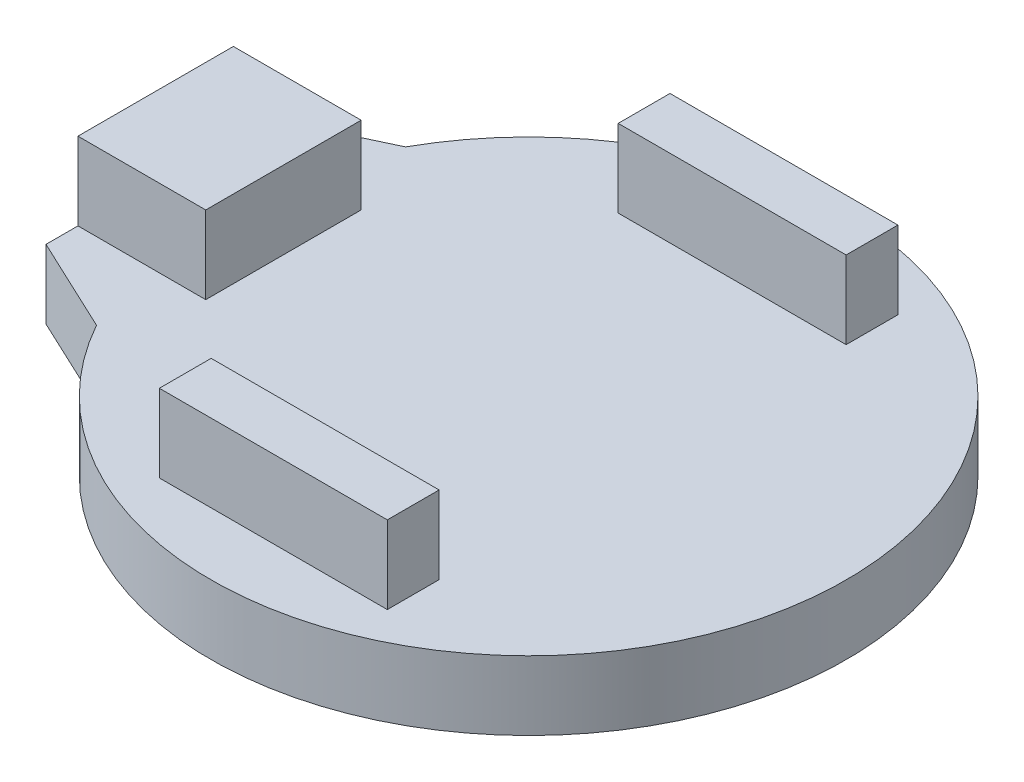
SolidWorks part; units mm, degrees
ref_plane "Front Plane" through (0, 0, 0) normal (0, 0, 1) x (1, 0, 0)
ref_plane "Top Plane" through (0, 0, 0) normal (0, 1, 0) x (1, 0, 0)
ref_plane "Right Plane" through (0, 0, 0) normal (1, 0, 0) x (0, 0, -1)
sketch "Sketch1" plane through (0, 0, 0) normal (0, 1, 0) x (1, 0, 0)
  line L0 (18.4, 0) -> (18.4, 26.4174) construction
  line L1 (-15.2, -6.35) -> (-17.2696, -6.35) construction
  line L2 (-15.2, -6.35) -> (-15.2, 6.35) construction
  line L3 (-17.2696, 6.35) -> (-21.6, 6.35) construction
  line L4 (-21.6, -6.35) -> (-21.6, 6.35)
  line L5 (-18.4, 0) -> (-21.6, 6.35) construction
  line L6 (-18.4, 0) -> (-21.6, -6.35) construction
  line L7 (-21.6, 6.35) -> (-16.0794, 8.9449)
  line L8 (-21.6, -6.35) -> (-16.0794, -8.9449)
  line L9 (-15.2, 6.35) -> (-17.2696, 6.35) construction
  line L10 (-15.2, 6.35) -> (-18.4, 0) construction
  line L11 (-15.2, -6.35) -> (-18.4, 0) construction
  line L12 (-17.2696, -6.35) -> (-21.6, -6.35) construction
  arc A0 (-16.0794, -8.9449) -> (-16.0794, 8.9449) centre (0, 0) ccw
  arc A1 (-16.0794, 8.9449) -> (-17.2696, 6.35) centre (0, 0) ccw construction
  arc A2 (-17.2696, 6.35) -> (-18.4, 0) centre (0, 0) ccw construction
  arc A3 (-18.4, 0) -> (-17.2696, -6.35) centre (0, 0) ccw construction
  arc A4 (-17.2696, -6.35) -> (-16.0794, -8.9449) centre (0, 0) ccw construction
  point P3 (-18.4, 0)
  point P14 (-14.75, 9.6822)
  dimension "D1" = 36.8
  dimension "D2" = 40
  dimension "D3" = 12.7
  dimension "D4" = 6.1
extrude "Boss-Extrude1" add sketch "Sketch1" along normal blind 4
sketch "Sketch2" plane through (0, 4, 0) normal (0, 1, 0) x (1, 0, 0)
  line L0 (0, -13.285) -> (0, 13.285) construction
  line L1 (-6.6, 14.785) -> (6.6, 14.785)
  line L2 (-6.6, 14.785) -> (-6.6, 11.785)
  line L3 (-6.6, 11.785) -> (6.6, 11.785)
  line L4 (6.6, 14.785) -> (6.6, 11.785)
  line L5 (-6.6, 14.785) -> (6.6, 11.785) construction
  line L6 (-6.6, 11.785) -> (6.6, 14.785) construction
  line L7 (-6.6, -11.785) -> (6.6, -11.785)
  line L8 (-6.6, -11.785) -> (-6.6, -14.785)
  line L9 (-6.6, -14.785) -> (6.6, -14.785)
  line L10 (6.6, -11.785) -> (6.6, -14.785)
  line L11 (-6.6, -11.785) -> (6.6, -14.785) construction
  line L12 (-6.6, -14.785) -> (6.6, -11.785) construction
  line L13 (-14.2, 0) -> (0, 0) construction
  line L14 (-21.6, -4.5) -> (-14.2, -4.5)
  line L15 (-21.6, -4.5) -> (-21.6, 4.5)
  line L16 (-21.6, 4.5) -> (-14.2, 4.5)
  line L17 (-14.2, -4.5) -> (-14.2, 4.5)
  line L18 (-21.6, -4.5) -> (-14.2, 4.5) construction
  line L19 (-21.6, 4.5) -> (-14.2, -4.5) construction
  line L20 (-21.6, 6.35) -> (-21.6, -6.35) construction
  point P0 (0, 13.285)
  point P5 (0, -13.285)
  point P16 (0, 0)
  point P19 (-17.9, 0)
  dimension "D1" = 26.57
  dimension "D2" = 3
  dimension "D3" = 13.2
  dimension "D4" = 9
  dimension "D5" = 7.4
extrude "Boss-Extrude2" add sketch "Sketch2" along normal blind 4.5
